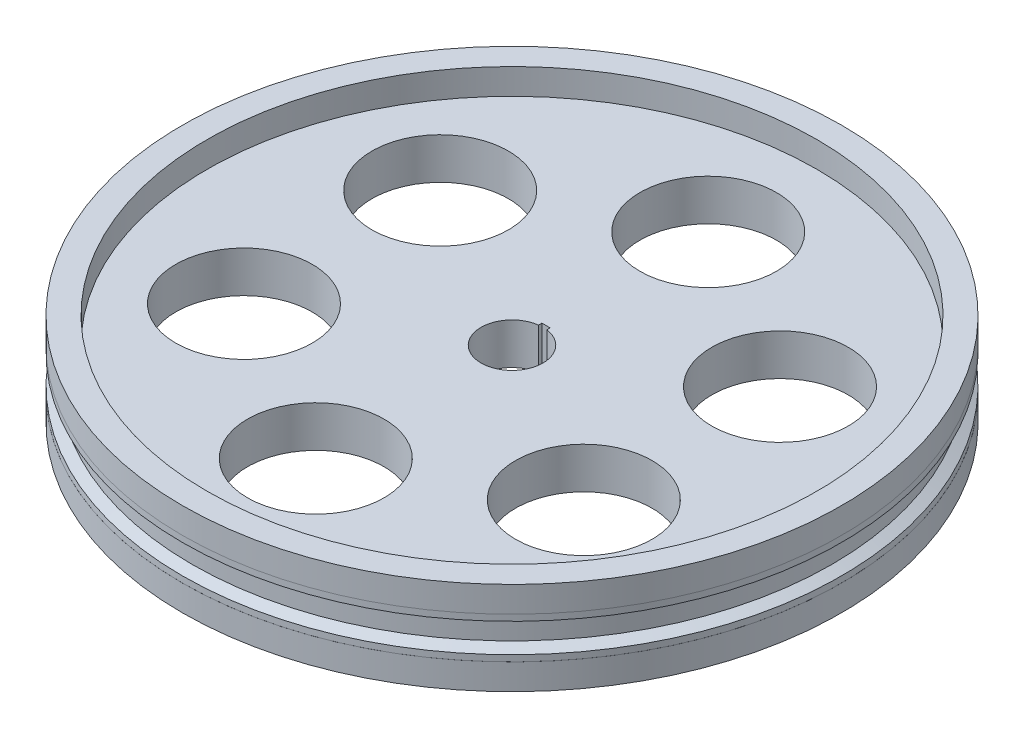
SolidWorks part; units mm, degrees
ref_plane "Alzado" through (0, 0, 0) normal (0, 0, 1) x (1, 0, 0)
ref_plane "Planta" through (0, 0, 0) normal (0, 1, 0) x (1, 0, 0)
ref_plane "Vista lateral" through (0, 0, 0) normal (1, 0, 0) x (0, 0, -1)
sketch "Croquis1" plane through (0, 0, 0) normal (0, 1, 0) x (1, 0, 0)
  line L0 (0, 0) -> (0, 15) construction
  line L1 (0, 0) -> (0, 155) construction
  line L2 (-2, 16.5) -> (2, 16.5)
  line L3 (-2, 16.5) -> (-2, 14.8661)
  line L5 (2, 16.5) -> (2, 14.8661)
  arc A0 (-2, 14.8661) -> (2, 14.8661) centre (0, 0) ccw
  circle A1 centre (0, 0) radius 155
  circle A2 centre (0, 95.0596) radius 33.0759
  circle A3 centre (82.324, 47.5298) radius 33.0759
  circle A4 centre (82.324, -47.5298) radius 33.0759
  circle A5 centre (0, -95.0596) radius 33.0759
  circle A6 centre (-82.324, -47.5298) radius 33.0759
  circle A7 centre (-82.324, 47.5298) radius 33.0759
  point P24 (0, 0)
  dimension "D1" = 30
  dimension "D2" = 310
  dimension "D3" = 4
extrude "Saliente-Extruir1" add sketch "Croquis1" along normal mid plane 20
ref_axis "Eje1" through (0, 10, 0) along (0, -1, 0)
sketch "Croquis2" plane through (0, 0, 0) normal (1, 0, 0) x (0, 0, -1)
  line L0 (155, 10) -> (155, 4.5)
  line L1 (155, -10) -> (155, 10) construction
  line L2 (155, -4.5) -> (155, -10)
  line L3 (155, 10) -> (-155, 10) construction
  line L4 (-155, -10) -> (155, -10) construction
  line L5 (155, 10) -> (159.6418, 10)
  line L6 (159.6418, 10) -> (159.6418, 7)
  line L7 (159.6418, 7) -> (155, 4.5)
  line L8 (159.6418, -7) -> (155, -4.5)
  line L9 (159.6418, -10) -> (159.6418, -7)
  line L10 (155, -10) -> (159.6418, -10)
  point P8 (155, 0)
  dimension "D1" = 9
  dimension "D2" = 5.5
  dimension "D3" = 5.5
  dimension "D4" = 3
revolve "Revolución1" add sketch "Croquis2" angle 360 about axis through (0, 10, 0) along (0, -1, 0)
sketch "Croquis3" plane through (0, 10, 0) normal (0, 1, 0) x (1, 0, 0)
  circle A0 centre (0, 0) radius 159.6652
  circle A1 centre (0, 0) radius 147.6652
  dimension "D1" = 12
extrude "Saliente-Extruir2" add sketch "Croquis3" along normal blind 12.5
mirror "Simetría1" about plane through (0, 0, 0) normal (0, 1, 0) of "Saliente-Extruir2"
